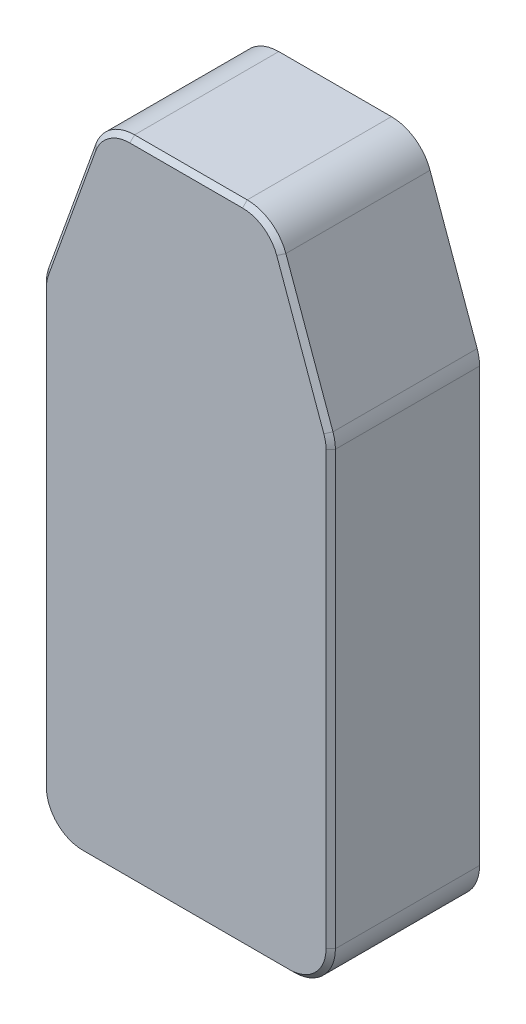
SolidWorks part; units mm, degrees
ref_plane "Front Plane" through (0, 0, 0) normal (0, 0, 1) x (1, 0, 0)
ref_plane "Top Plane" through (0, 0, 0) normal (0, 1, 0) x (1, 0, 0)
ref_plane "Right Plane" through (0, 0, 0) normal (1, 0, 0) x (0, 0, -1)
sketch "Sketch1" plane through (0, 0, 0) normal (0, 0, 1) x (1, 0, 0)
  line L36 (-30.2974, 123.4372) -> (-45.3256, 81.692)
  line L37 (-46.1, 77.2548) -> (-46.1, -60.7336)
  line L38 (-33, -73.8336) -> (33, -73.8336)
  line L39 (46.1, -60.7336) -> (46.1, 77.2548)
  line L40 (45.3256, 81.692) -> (30.2974, 123.4372)
  line L41 (17.9717, 132.1) -> (-17.9717, 132.1)
  line L42 (-27.4747, 122.4211) -> (-42.503, 80.6759)
  line L43 (-43.1, 77.2548) -> (-43.1, -60.7336)
  line L44 (-33, -70.8336) -> (33, -70.8336)
  line L45 (43.1, -60.7336) -> (43.1, 77.2548)
  line L46 (42.503, 80.6759) -> (27.4747, 122.4211)
  line L47 (17.9717, 129.1) -> (-17.9717, 129.1)
  line L48 (-27.4747, 122.4211) -> (-42.503, 80.6759)
  line L49 (-43.1, 77.2548) -> (-43.1, -60.7336)
  line L50 (-33, -70.8336) -> (33, -70.8336)
  line L51 (43.1, -60.7336) -> (43.1, 77.2548)
  line L52 (42.503, 80.6759) -> (27.4747, 122.4211)
  line L53 (17.9717, 129.1) -> (-17.9717, 129.1)
  arc A42 (-45.3256, 81.692) -> (-46.1, 77.2548) centre (-33, 77.2548) ccw
  arc A43 (-46.1, -60.7336) -> (-33, -73.8336) centre (-33, -60.7336) ccw
  arc A44 (33, -73.8336) -> (46.1, -60.7336) centre (33, -60.7336) ccw
  arc A45 (46.1, 77.2548) -> (45.3256, 81.692) centre (33, 77.2548) ccw
  arc A46 (30.2974, 123.4372) -> (17.9717, 132.1) centre (17.9717, 119) ccw
  arc A47 (-17.9717, 132.1) -> (-30.2974, 123.4372) centre (-17.9717, 119) ccw
  arc A48 (-42.503, 80.6759) -> (-43.1, 77.2548) centre (-33, 77.2548) ccw
  arc A49 (-43.1, -60.7336) -> (-33, -70.8336) centre (-33, -60.7336) ccw
  arc A50 (33, -70.8336) -> (43.1, -60.7336) centre (33, -60.7336) ccw
  arc A51 (43.1, 77.2548) -> (42.503, 80.6759) centre (33, 77.2548) ccw
  arc A52 (27.4747, 122.4211) -> (17.9717, 129.1) centre (17.9717, 119) ccw
  arc A53 (-17.9717, 129.1) -> (-27.4747, 122.4211) centre (-17.9717, 119) ccw
  arc A54 (-42.503, 80.6759) -> (-43.1, 77.2548) centre (-33, 77.2548) ccw
  arc A55 (-43.1, -60.7336) -> (-33, -70.8336) centre (-33, -60.7336) ccw
  arc A56 (33, -70.8336) -> (43.1, -60.7336) centre (33, -60.7336) ccw
  arc A57 (43.1, 77.2548) -> (42.503, 80.6759) centre (33, 77.2548) ccw
  arc A58 (27.4747, 122.4211) -> (17.9717, 129.1) centre (17.9717, 119) ccw
  arc A59 (-17.9717, 129.1) -> (-27.4747, 122.4211) centre (-17.9717, 119) ccw
  dimension "D1" = 0.1
  dimension "D2" = 3
extrude "Boss-Extrude1" add sketch "Sketch1" along normal blind 46
sketch "Sketch2" plane through (0, 0, 46) normal (0, 0, 1) x (1, 0, 0)
  line L6 (17.9717, 132.1) -> (-17.9717, 132.1)
  line L7 (-30.2974, 123.4372) -> (-45.3256, 81.692)
  line L8 (-46.1, 77.2548) -> (-46.1, -60.7336)
  line L9 (-33, -73.8336) -> (33, -73.8336)
  line L10 (46.1, -60.7336) -> (46.1, 77.2548)
  line L11 (45.3256, 81.692) -> (30.2974, 123.4372)
  line L12 (17.9717, 132.1) -> (-17.9717, 132.1)
  line L13 (-30.2974, 123.4372) -> (-45.3256, 81.692)
  line L14 (-46.1, 77.2548) -> (-46.1, -60.7336)
  line L15 (-33, -73.8336) -> (33, -73.8336)
  line L16 (46.1, -60.7336) -> (46.1, 77.2548)
  line L17 (45.3256, 81.692) -> (30.2974, 123.4372)
  arc A6 (-17.9717, 132.1) -> (-30.2974, 123.4372) centre (-17.9717, 119) ccw
  arc A7 (-45.3256, 81.692) -> (-46.1, 77.2548) centre (-33, 77.2548) ccw
  arc A8 (-46.1, -60.7336) -> (-33, -73.8336) centre (-33, -60.7336) ccw
  arc A9 (33, -73.8336) -> (46.1, -60.7336) centre (33, -60.7336) ccw
  arc A10 (46.1, 77.2548) -> (45.3256, 81.692) centre (33, 77.2548) ccw
  arc A11 (30.2974, 123.4372) -> (17.9717, 132.1) centre (17.9717, 119) ccw
  arc A12 (-17.9717, 132.1) -> (-30.2974, 123.4372) centre (-17.9717, 119) ccw
  arc A13 (-45.3256, 81.692) -> (-46.1, 77.2548) centre (-33, 77.2548) ccw
  arc A14 (-46.1, -60.7336) -> (-33, -73.8336) centre (-33, -60.7336) ccw
  arc A15 (33, -73.8336) -> (46.1, -60.7336) centre (33, -60.7336) ccw
  arc A16 (46.1, 77.2548) -> (45.3256, 81.692) centre (33, 77.2548) ccw
  arc A17 (30.2974, 123.4372) -> (17.9717, 132.1) centre (17.9717, 119) ccw
  dimension "D1" = 0
extrude "Boss-Extrude2" add sketch "Sketch2" along normal blind 1.5
chamfer "Chamfer1" distance 1.5 angle 45 24 edges at (37.8115, 102.5646, 47.5) (45.905, 79.507, 47.5) (46.1, 8.2606, 47.5) (42.2631, -69.9967, 47.5) (0, -73.8336, 47.5) (-42.2631, -69.9967, 47.5) (-46.1, 8.2606, 47.5) (-45.905, 79.507, 47.5) (-37.8115, 102.5646, 47.5) (-25.5044, 129.7177, 47.5) (0, 132.1, 47.5) (25.5044, 129.7177, 47.5) (0, -70.8336, 0) (40.1418, -67.8754, 0) (-40.1418, -67.8754, 0) (43.1, 8.2606, 0) (-43.1, 8.2606, 0) (42.9496, 78.9912, 0) (-42.9496, 78.9912, 0) (34.9888, 101.5485, 0) (-34.9888, 101.5485, 0) (23.7794, 127.2633, 0) (-23.7794, 127.2633, 0) (0, 129.1, 0)
